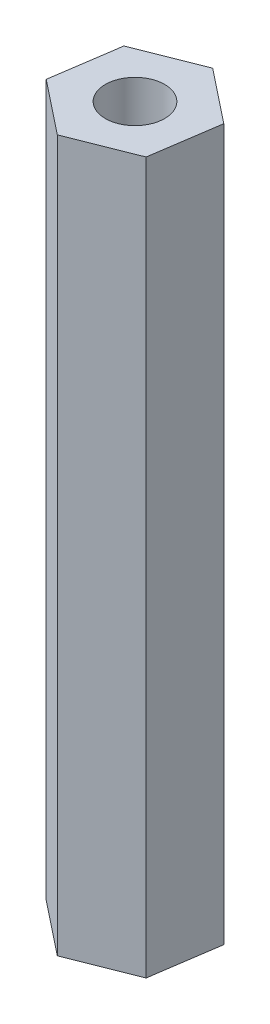
SolidWorks part; units mm, degrees
ref_plane "Front Plane" through (0, 0, 0) normal (0, 0, 1) x (1, 0, 0)
ref_plane "Top Plane" through (0, 0, 0) normal (0, 1, 0) x (1, 0, 0)
ref_plane "Right Plane" through (0, 0, 0) normal (1, 0, 0) x (0, 0, -1)
sketch "Sketch1" plane through (0, 0, 0) normal (0, 1, 0) x (1, 0, 0)
  line L1 (2.716, -2.1502) -> (3.2201, 1.277)
  line L2 (3.2201, 1.277) -> (0.5041, 3.4272)
  line L3 (0.5041, 3.4272) -> (-2.716, 2.1502)
  line L4 (-2.716, 2.1502) -> (-3.2201, -1.277)
  line L5 (-3.2201, -1.277) -> (-0.5041, -3.4272)
  line L6 (-0.5041, -3.4272) -> (2.716, -2.1502)
  circle A0 centre (0, 0) radius 3 construction
  circle A1 centre (0, 0) radius 1.5
  dimension "D2" = 3
  dimension "D1" = 6
extrude "Boss-Extrude1" add sketch "Sketch1" along normal blind 36
